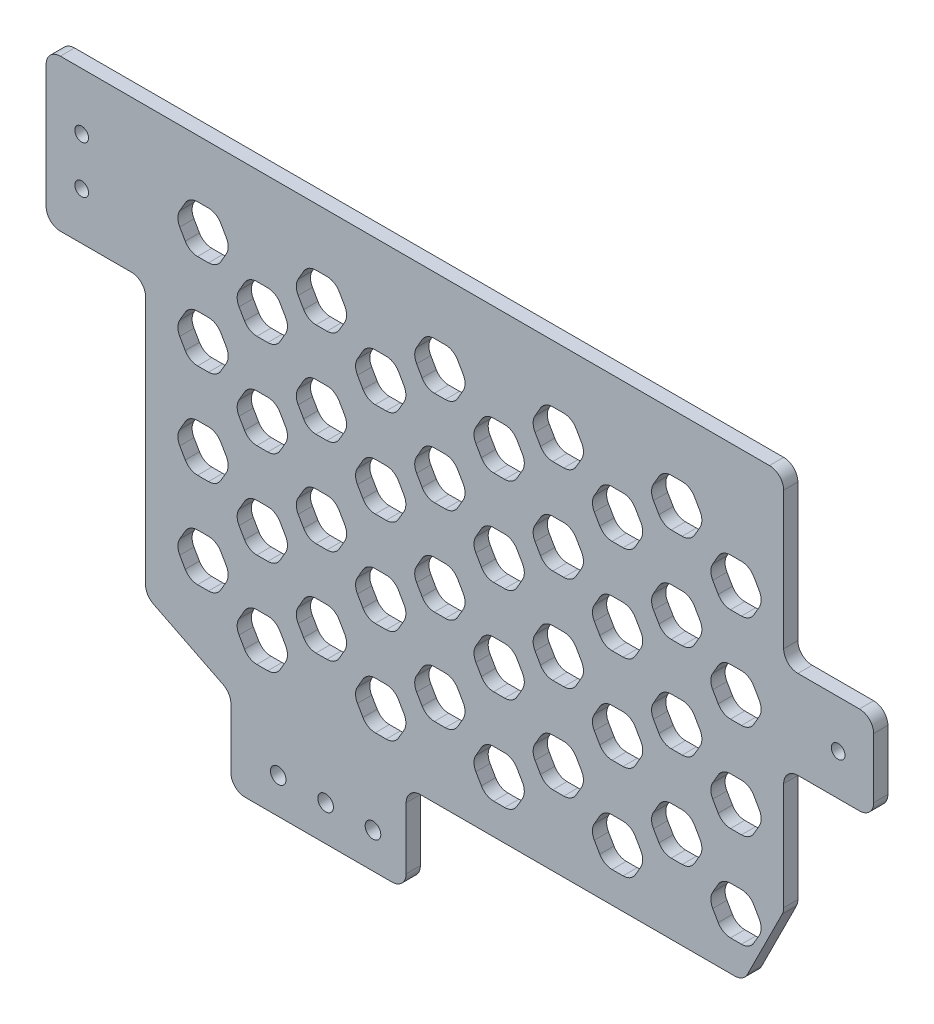
SolidWorks part; units mm, degrees
material "轻木"
ref_plane "前视基准面" through (0, 0, 0) normal (0, 0, 1) x (1, 0, 0)
ref_plane "上视基准面" through (0, 0, 0) normal (0, 1, 0) x (1, 0, 0)
ref_plane "右视基准面" through (0, 0, 0) normal (1, 0, 0) x (0, 0, -1)
other "Configuration Table"
sketch "草图1" plane through (0, 0, 0) normal (0, 0, 1) x (1, 0, 0)
  line L0 (45, -487.5) -> (65, -487.5) construction
  line L1 (415, -487.5) -> (-185, -487.5) construction
  line L2 (65, -487.5) -> (65, -367.5) construction
  line L3 (230, -367.5) -> (0, -367.5) construction
  line L4 (65, -367.5) -> (134.7, -367.5) construction
  line L5 (131.6098, -367.5) -> (70, -367.5) construction
  line L6 (134.7, -367.5) -> (144.6985, -347.503) construction
  line L7 (144.6985, -367.5) -> (144.6985, -7.5) construction
  line L9 (144.6985, -297.5) -> (144.6985, -262.5) construction
  line L10 (144.6985, -262.5) -> (-15, -262.5) construction
  line L11 (-15, -262.5) -> (-15, -302.5) construction
  line L12 (-15, -472.5) -> (-15, 97.5) construction
  line L13 (-15, -302.5) -> (2, -302.5) construction
  line L14 (2, -302.5) -> (2, -347.5) construction
  line L15 (2, -347.5) -> (2, -358.5) construction
  line L16 (17.2361, -366.118) -> (1.0557, -358.0279) construction
  line L17 (2, -358.5) -> (20, -367.5) construction
  line L18 (20, -367.5) -> (20, -382.5) construction
  line L19 (230, -382.5) -> (0, -382.5) construction
  line L20 (20, -382.5) -> (0, -392.5) construction
  line L21 (0, -472.5) -> (0, 97.5) construction
  line L22 (0, -392.5) -> (-15, -392.5) construction
  line L23 (-15, -392.5) -> (-15, -453.5) construction
  line L24 (-15, -453.5) -> (0, -453.5) construction
  line L25 (0, -453.5) -> (0, -470.5) construction
  line L26 (0, -470.5) -> (45, -470.5) construction
  line L27 (45, -470.5) -> (45, -487.5) construction
  line L28 (144.6985, -347.503) -> (144.6985, -324.1459) construction
  line L29 (144.6985, -324.1459) -> (159.7, -324.1459) construction
  line L30 (159.7, -324.1459) -> (159.6985, -297.5) construction
  line L31 (159.6985, -367.5) -> (159.6985, -7.5) construction
  line L32 (159.6985, -297.5) -> (144.6985, -297.5) construction
  line L33 (149.6985, -262.5) -> (158.5181, -262.5) construction
  line L35 (158.5181, -297.5) -> (149.6985, -297.5) construction
  line L36 (143.318, -350.2639) -> (136.082, -364.7361) construction
  line L37 (65, -372.5) -> (65, -482.5) construction
  line L40 (-4, -453.5) -> (-11, -453.5) construction
  line L41 (-10, -392.5) -> (-1.1803, -392.5) construction
  line L42 (1.0557, -391.9721) -> (17.2361, -383.882) construction
  line L43 (140.6985, -301.5) -> (140.6985, -266.5) construction
  line L44 (140.6985, -266.5) -> (-11, -266.5) construction
  line L45 (-11, -266.5) -> (-11, -298.5) construction
  line L46 (-11, -298.5) -> (6, -298.5) construction
  line L47 (6, -298.5) -> (6, -347.5) construction
  line L48 (6, -347.5) -> (6, -356.0279) construction
  line L49 (6, -356.0279) -> (24, -365.0279) construction
  line L50 (24, -365.0279) -> (24, -384.9721) construction
  line L51 (24, -384.9721) -> (0.9443, -396.5) construction
  line L52 (0.9443, -396.5) -> (-11, -396.5) construction
  line L53 (-11, -396.5) -> (-11, -449.5) construction
  line L54 (-11, -449.5) -> (4, -449.5) construction
  line L55 (4, -449.5) -> (4, -466.5) construction
  line L56 (4, -466.5) -> (49, -466.5) construction
  line L57 (49, -466.5) -> (49, -483.5) construction
  line L58 (49, -483.5) -> (61, -483.5) construction
  line L59 (61, -483.5) -> (61, -363.5) construction
  line L60 (61, -363.5) -> (132.2279, -363.5) construction
  line L61 (132.2279, -363.5) -> (140.6985, -346.5588) construction
  line L62 (140.6985, -346.5588) -> (140.6985, -320.1459) construction
  line L63 (140.6985, -320.1459) -> (155.6998, -320.1459) construction
  line L64 (155.6998, -320.1459) -> (155.6987, -301.5) construction
  line L65 (155.6987, -301.5) -> (140.6985, -301.5) construction
  line L66 (-15, -266.5) -> (140.6985, -266.5)
  line L67 (140.6985, -266.5) -> (140.6985, -301.5)
  line L68 (140.6985, -301.5) -> (159.6987, -301.5)
  line L69 (159.6987, -301.5) -> (159.6998, -320.1459)
  line L70 (159.6998, -320.1459) -> (140.6985, -320.1459)
  line L71 (140.6985, -320.1459) -> (140.6985, -346.5588)
  line L72 (140.6985, -346.5588) -> (132.2279, -363.5)
  line L73 (132.2279, -363.5) -> (61, -363.5)
  line L74 (61, -363.5) -> (61, -487.5)
  line L75 (61, -487.5) -> (49, -487.5)
  line L76 (49, -487.5) -> (49, -466.5)
  line L77 (49, -466.5) -> (4, -466.5)
  line L78 (4, -466.5) -> (4, -449.5)
  line L79 (4, -449.5) -> (-15, -449.5)
  line L80 (-15, -449.5) -> (-15, -396.5)
  line L81 (-15, -396.5) -> (0.9443, -396.5)
  line L82 (0.9443, -396.5) -> (24, -384.9721)
  line L83 (24, -384.9721) -> (24, -365.0279)
  line L84 (24, -365.0279) -> (6, -356.0279)
  line L85 (6, -356.0279) -> (6, -298.5)
  line L86 (6, -298.5) -> (-15, -298.5)
  line L87 (-15, -298.5) -> (-15, -266.5)
  dimension "D1" = 4
extrude "凸台-拉伸1" add sketch "草图1" along normal blind 3
sketch "草图2" plane through (0, 0, 3) normal (0, 0, 1) x (1, 0, 0)
  line L2 (-7.5, -251.7939) -> (-7.5, -517.3425) construction
  line L3 (16.6902, -480) -> (92.3332, -480) construction
  line L4 (-15, -298.5) -> (6, -298.5) construction
  line L6 (49, -487.5) -> (61, -487.5) construction
  line L8 (-15, -396.5) -> (-15, -449.5) construction
  line L13 (159.6998, -320.1459) -> (159.6987, -301.5) construction
  line L14 (159.6987, -301.5) -> (140.6985, -301.5) construction
  line L17 (49, -466.5) -> (49, -487.5) construction
  circle A0 centre (-7.5, -415) radius 1.45
  circle A1 centre (-7.5, -439.5) radius 1.45
  circle A2 centre (56, -480) radius 1.45
  circle A5 centre (152.1993, -311.5) radius 1.45
  circle A7 centre (-7.5, -288.5) radius 1.45
  circle A8 centre (-7.5, -278.5) radius 1.45
  dimension "D5" = 126.5
  dimension "D8" = 10
  dimension "D11" = 7
  dimension "D12" = 2.9
  dimension "D13" = 10
  dimension "D14" = 10
  dimension "D3" = 2.9
  dimension "D4" = 24.5
  dimension "D1" = 7.5
  dimension "D2" = 7.5
  dimension "D7" = 7.5
extrude "切除-拉伸1" cut sketch "草图2" against normal through all
fillet "圆角3" radius 3 22 edges at (159.6998, -320.1459, 1.5) (140.6985, -320.1459, 1.5) (61, -487.5, 1.5) (49, -487.5, 1.5) (49, -466.5, 1.5) (4, -466.5, 1.5) (4, -449.5, 1.5) (-15, -449.5, 1.5) (-15, -396.5, 1.5) (0.9443, -396.5, 1.5) (24, -384.9721, 1.5) (24, -365.0279, 1.5) (6, -356.0279, 1.5) (6, -298.5, 1.5) (-15, -298.5, 1.5) (-15, -266.5, 1.5) (140.6985, -266.5, 1.5) (140.6985, -301.5, 1.5) (159.6987, -301.5, 1.5) (140.6985, -346.5588, 1.5) (132.2279, -363.5, 1.5) (61, -363.5, 1.5)
sketch "草图3" plane through (0, 0, 0) normal (0, 0, -1) x (-1, 0, 0)
  circle A0 centre (-34, -375) radius 1.65 construction
  circle A1 centre (-44, -375) radius 1.65 construction
  circle A2 centre (-54, -375) radius 1.65 construction
  circle A3 centre (-34, -375) radius 1.65
  circle A4 centre (-44, -375) radius 1.65
  circle A5 centre (-54, -375) radius 1.65
extrude "切除-拉伸2" cut sketch "草图3" against normal through all
sketch "草图4" plane through (0, 0, 3) normal (0, 0, 1) x (1, 0, 0)
  line L0 (48.8972, -283.6407) -> (46.0104, -278.6407)
  line L1 (23.8972, -283.6407) -> (21.0104, -278.6407)
  line L2 (21.0104, -278.6407) -> (15.2369, -278.6407)
  line L3 (15.2369, -278.6407) -> (12.3502, -283.6407)
  line L4 (12.3502, -283.6407) -> (15.2369, -288.6407)
  line L5 (15.2369, -288.6407) -> (21.0104, -288.6407)
  line L6 (21.0104, -288.6407) -> (23.8972, -283.6407)
  line L7 (36.4102, -291.9675) -> (33.5235, -286.9675)
  line L8 (33.5235, -286.9675) -> (27.75, -286.9675)
  line L9 (27.75, -286.9675) -> (24.8632, -291.9675)
  line L10 (24.8632, -291.9675) -> (27.75, -296.9675)
  line L11 (27.75, -296.9675) -> (33.5235, -296.9675)
  line L12 (33.5235, -296.9675) -> (36.4102, -291.9675)
  line L13 (46.0104, -278.6407) -> (40.2369, -278.6407)
  line L14 (40.2369, -278.6407) -> (37.3502, -283.6407)
  line L15 (37.3502, -283.6407) -> (40.2369, -288.6407)
  line L16 (40.2369, -288.6407) -> (46.0104, -288.6407)
  line L17 (46.0104, -288.6407) -> (48.8972, -283.6407)
  line L18 (61.4102, -291.9675) -> (58.5235, -286.9675)
  line L19 (58.5235, -286.9675) -> (52.75, -286.9675)
  line L20 (52.75, -286.9675) -> (49.8632, -291.9675)
  line L21 (49.8632, -291.9675) -> (52.75, -296.9675)
  line L22 (52.75, -296.9675) -> (58.5235, -296.9675)
  line L23 (58.5235, -296.9675) -> (61.4102, -291.9675)
  line L24 (73.8972, -283.6407) -> (71.0104, -278.6407)
  line L25 (71.0104, -278.6407) -> (65.2369, -278.6407)
  line L26 (65.2369, -278.6407) -> (62.3502, -283.6407)
  line L27 (62.3502, -283.6407) -> (65.2369, -288.6407)
  line L28 (65.2369, -288.6407) -> (71.0104, -288.6407)
  line L29 (71.0104, -288.6407) -> (73.8972, -283.6407)
  line L30 (86.4102, -291.9675) -> (83.5235, -286.9675)
  line L31 (83.5235, -286.9675) -> (77.75, -286.9675)
  line L32 (77.75, -286.9675) -> (74.8632, -291.9675)
  line L33 (74.8632, -291.9675) -> (77.75, -296.9675)
  line L34 (77.75, -296.9675) -> (83.5235, -296.9675)
  line L35 (83.5235, -296.9675) -> (86.4102, -291.9675)
  line L36 (98.8972, -283.6407) -> (96.0104, -278.6407)
  line L37 (96.0104, -278.6407) -> (90.2369, -278.6407)
  line L38 (90.2369, -278.6407) -> (87.3502, -283.6407)
  line L39 (87.3502, -283.6407) -> (90.2369, -288.6407)
  line L40 (90.2369, -288.6407) -> (96.0104, -288.6407)
  line L41 (96.0104, -288.6407) -> (98.8972, -283.6407)
  line L42 (111.4102, -291.9675) -> (108.5235, -286.9675)
  line L43 (108.5235, -286.9675) -> (102.75, -286.9675)
  line L44 (102.75, -286.9675) -> (99.8632, -291.9675)
  line L45 (99.8632, -291.9675) -> (102.75, -296.9675)
  line L46 (102.75, -296.9675) -> (108.5235, -296.9675)
  line L47 (108.5235, -296.9675) -> (111.4102, -291.9675)
  line L48 (123.8972, -283.6407) -> (121.0104, -278.6407)
  line L49 (121.0104, -278.6407) -> (115.2369, -278.6407)
  line L50 (115.2369, -278.6407) -> (112.3502, -283.6407)
  line L51 (112.3502, -283.6407) -> (115.2369, -288.6407)
  line L52 (115.2369, -288.6407) -> (121.0104, -288.6407)
  line L53 (121.0104, -288.6407) -> (123.8972, -283.6407)
  line L54 (136.4102, -291.9675) -> (133.5235, -286.9675)
  line L55 (133.5235, -286.9675) -> (127.75, -286.9675)
  line L56 (127.75, -286.9675) -> (124.8632, -291.9675)
  line L57 (124.8632, -291.9675) -> (127.75, -296.9675)
  line L58 (127.75, -296.9675) -> (133.5235, -296.9675)
  line L59 (133.5235, -296.9675) -> (136.4102, -291.9675)
  line L60 (48.8972, -303.6407) -> (46.0104, -298.6407)
  line L61 (46.0104, -298.6407) -> (40.2369, -298.6407)
  line L62 (40.2369, -298.6407) -> (37.3502, -303.6407)
  line L63 (37.3502, -303.6407) -> (40.2369, -308.6407)
  line L64 (40.2369, -308.6407) -> (46.0104, -308.6407)
  line L65 (46.0104, -308.6407) -> (48.8972, -303.6407)
  line L66 (61.4102, -311.9675) -> (58.5235, -306.9675)
  line L67 (58.5235, -306.9675) -> (52.75, -306.9675)
  line L68 (52.75, -306.9675) -> (49.8632, -311.9675)
  line L69 (49.8632, -311.9675) -> (52.75, -316.9675)
  line L70 (52.75, -316.9675) -> (58.5235, -316.9675)
  line L71 (58.5235, -316.9675) -> (61.4102, -311.9675)
  line L72 (73.8972, -303.6407) -> (71.0104, -298.6407)
  line L73 (71.0104, -298.6407) -> (65.2369, -298.6407)
  line L74 (65.2369, -298.6407) -> (62.3502, -303.6407)
  line L75 (62.3502, -303.6407) -> (65.2369, -308.6407)
  line L76 (65.2369, -308.6407) -> (71.0104, -308.6407)
  line L77 (71.0104, -308.6407) -> (73.8972, -303.6407)
  line L78 (86.4102, -311.9675) -> (83.5235, -306.9675)
  line L79 (83.5235, -306.9675) -> (77.75, -306.9675)
  line L80 (77.75, -306.9675) -> (74.8632, -311.9675)
  line L81 (74.8632, -311.9675) -> (77.75, -316.9675)
  line L82 (77.75, -316.9675) -> (83.5235, -316.9675)
  line L83 (83.5235, -316.9675) -> (86.4102, -311.9675)
  line L84 (98.8972, -303.6407) -> (96.0104, -298.6407)
  line L85 (96.0104, -298.6407) -> (90.2369, -298.6407)
  line L86 (90.2369, -298.6407) -> (87.3502, -303.6407)
  line L87 (87.3502, -303.6407) -> (90.2369, -308.6407)
  line L88 (90.2369, -308.6407) -> (96.0104, -308.6407)
  line L89 (96.0104, -308.6407) -> (98.8972, -303.6407)
  line L90 (111.4102, -311.9675) -> (108.5235, -306.9675)
  line L91 (108.5235, -306.9675) -> (102.75, -306.9675)
  line L92 (102.75, -306.9675) -> (99.8632, -311.9675)
  line L93 (99.8632, -311.9675) -> (102.75, -316.9675)
  line L94 (102.75, -316.9675) -> (108.5235, -316.9675)
  line L95 (108.5235, -316.9675) -> (111.4102, -311.9675)
  line L96 (123.8972, -303.6407) -> (121.0104, -298.6407)
  line L97 (121.0104, -298.6407) -> (115.2369, -298.6407)
  line L98 (115.2369, -298.6407) -> (112.3502, -303.6407)
  line L99 (112.3502, -303.6407) -> (115.2369, -308.6407)
  line L100 (115.2369, -308.6407) -> (121.0104, -308.6407)
  line L101 (121.0104, -308.6407) -> (123.8972, -303.6407)
  line L102 (136.4102, -311.9675) -> (133.5235, -306.9675)
  line L103 (133.5235, -306.9675) -> (127.75, -306.9675)
  line L104 (127.75, -306.9675) -> (124.8632, -311.9675)
  line L105 (124.8632, -311.9675) -> (127.75, -316.9675)
  line L106 (127.75, -316.9675) -> (133.5235, -316.9675)
  line L107 (133.5235, -316.9675) -> (136.4102, -311.9675)
  line L108 (48.8972, -323.6407) -> (46.0104, -318.6407)
  line L109 (46.0104, -318.6407) -> (40.2369, -318.6407)
  line L110 (40.2369, -318.6407) -> (37.3502, -323.6407)
  line L111 (37.3502, -323.6407) -> (40.2369, -328.6407)
  line L112 (40.2369, -328.6407) -> (46.0104, -328.6407)
  line L113 (46.0104, -328.6407) -> (48.8972, -323.6407)
  line L114 (61.4102, -331.9675) -> (58.5235, -326.9675)
  line L115 (58.5235, -326.9675) -> (52.75, -326.9675)
  line L116 (52.75, -326.9675) -> (49.8632, -331.9675)
  line L117 (49.8632, -331.9675) -> (52.75, -336.9675)
  line L118 (52.75, -336.9675) -> (58.5235, -336.9675)
  line L119 (58.5235, -336.9675) -> (61.4102, -331.9675)
  line L120 (73.8972, -323.6407) -> (71.0104, -318.6407)
  line L121 (71.0104, -318.6407) -> (65.2369, -318.6407)
  line L122 (65.2369, -318.6407) -> (62.3502, -323.6407)
  line L123 (62.3502, -323.6407) -> (65.2369, -328.6407)
  line L124 (65.2369, -328.6407) -> (71.0104, -328.6407)
  line L125 (71.0104, -328.6407) -> (73.8972, -323.6407)
  line L126 (86.4102, -331.9675) -> (83.5235, -326.9675)
  line L127 (83.5235, -326.9675) -> (77.75, -326.9675)
  line L128 (77.75, -326.9675) -> (74.8632, -331.9675)
  line L129 (74.8632, -331.9675) -> (77.75, -336.9675)
  line L130 (77.75, -336.9675) -> (83.5235, -336.9675)
  line L131 (83.5235, -336.9675) -> (86.4102, -331.9675)
  line L132 (98.8972, -323.6407) -> (96.0104, -318.6407)
  line L133 (96.0104, -318.6407) -> (90.2369, -318.6407)
  line L134 (90.2369, -318.6407) -> (87.3502, -323.6407)
  line L135 (87.3502, -323.6407) -> (90.2369, -328.6407)
  line L136 (90.2369, -328.6407) -> (96.0104, -328.6407)
  line L137 (96.0104, -328.6407) -> (98.8972, -323.6407)
  line L138 (111.4102, -331.9675) -> (108.5235, -326.9675)
  line L139 (108.5235, -326.9675) -> (102.75, -326.9675)
  line L140 (102.75, -326.9675) -> (99.8632, -331.9675)
  line L141 (99.8632, -331.9675) -> (102.75, -336.9675)
  line L142 (102.75, -336.9675) -> (108.5235, -336.9675)
  line L143 (108.5235, -336.9675) -> (111.4102, -331.9675)
  line L144 (123.8972, -323.6407) -> (121.0104, -318.6407)
  line L145 (121.0104, -318.6407) -> (115.2369, -318.6407)
  line L146 (115.2369, -318.6407) -> (112.3502, -323.6407)
  line L147 (112.3502, -323.6407) -> (115.2369, -328.6407)
  line L148 (115.2369, -328.6407) -> (121.0104, -328.6407)
  line L149 (121.0104, -328.6407) -> (123.8972, -323.6407)
  line L150 (136.4102, -331.9675) -> (133.5235, -326.9675)
  line L151 (133.5235, -326.9675) -> (127.75, -326.9675)
  line L152 (127.75, -326.9675) -> (124.8632, -331.9675)
  line L153 (124.8632, -331.9675) -> (127.75, -336.9675)
  line L154 (127.75, -336.9675) -> (133.5235, -336.9675)
  line L155 (133.5235, -336.9675) -> (136.4102, -331.9675)
  line L156 (48.8972, -343.6407) -> (46.0104, -338.6407)
  line L157 (46.0104, -338.6407) -> (40.2369, -338.6407)
  line L158 (40.2369, -338.6407) -> (37.3502, -343.6407)
  line L159 (37.3502, -343.6407) -> (40.2369, -348.6407)
  line L160 (40.2369, -348.6407) -> (46.0104, -348.6407)
  line L161 (46.0104, -348.6407) -> (48.8972, -343.6407)
  line L162 (61.4102, -351.9675) -> (58.5235, -346.9675)
  line L163 (58.5235, -346.9675) -> (52.75, -346.9675)
  line L164 (52.75, -346.9675) -> (49.8632, -351.9675)
  line L165 (49.8632, -351.9675) -> (52.75, -356.9675)
  line L166 (52.75, -356.9675) -> (58.5235, -356.9675)
  line L167 (58.5235, -356.9675) -> (61.4102, -351.9675)
  line L168 (73.8972, -343.6407) -> (71.0104, -338.6407)
  line L169 (71.0104, -338.6407) -> (65.2369, -338.6407)
  line L170 (65.2369, -338.6407) -> (62.3502, -343.6407)
  line L171 (62.3502, -343.6407) -> (65.2369, -348.6407)
  line L172 (65.2369, -348.6407) -> (71.0104, -348.6407)
  line L173 (71.0104, -348.6407) -> (73.8972, -343.6407)
  line L174 (86.4102, -351.9675) -> (83.5235, -346.9675)
  line L175 (83.5235, -346.9675) -> (77.75, -346.9675)
  line L176 (77.75, -346.9675) -> (74.8632, -351.9675)
  line L177 (74.8632, -351.9675) -> (77.75, -356.9675)
  line L178 (77.75, -356.9675) -> (83.5235, -356.9675)
  line L179 (83.5235, -356.9675) -> (86.4102, -351.9675)
  line L180 (98.8972, -343.6407) -> (96.0104, -338.6407)
  line L181 (96.0104, -338.6407) -> (90.2369, -338.6407)
  line L182 (90.2369, -338.6407) -> (87.3502, -343.6407)
  line L183 (87.3502, -343.6407) -> (90.2369, -348.6407)
  line L184 (90.2369, -348.6407) -> (96.0104, -348.6407)
  line L185 (96.0104, -348.6407) -> (98.8972, -343.6407)
  line L186 (111.4102, -351.9675) -> (108.5235, -346.9675)
  line L187 (108.5235, -346.9675) -> (102.75, -346.9675)
  line L188 (102.75, -346.9675) -> (99.8632, -351.9675)
  line L189 (99.8632, -351.9675) -> (102.75, -356.9675)
  line L190 (102.75, -356.9675) -> (108.5235, -356.9675)
  line L191 (108.5235, -356.9675) -> (111.4102, -351.9675)
  line L192 (123.8972, -343.6407) -> (121.0104, -338.6407)
  line L193 (121.0104, -338.6407) -> (115.2369, -338.6407)
  line L194 (115.2369, -338.6407) -> (112.3502, -343.6407)
  line L195 (112.3502, -343.6407) -> (115.2369, -348.6407)
  line L196 (115.2369, -348.6407) -> (121.0104, -348.6407)
  line L197 (121.0104, -348.6407) -> (123.8972, -343.6407)
  line L198 (136.4102, -351.9675) -> (133.5235, -346.9675)
  line L199 (133.5235, -346.9675) -> (127.75, -346.9675)
  line L200 (127.75, -346.9675) -> (124.8632, -351.9675)
  line L201 (124.8632, -351.9675) -> (127.75, -356.9675)
  line L202 (127.75, -356.9675) -> (133.5235, -356.9675)
  line L203 (133.5235, -356.9675) -> (136.4102, -351.9675)
  line L204 (23.8972, -303.6407) -> (21.0104, -298.6407)
  line L205 (21.0104, -298.6407) -> (15.2369, -298.6407)
  line L206 (15.2369, -298.6407) -> (12.3502, -303.6407)
  line L207 (12.3502, -303.6407) -> (15.2369, -308.6407)
  line L208 (15.2369, -308.6407) -> (21.0104, -308.6407)
  line L209 (21.0104, -308.6407) -> (23.8972, -303.6407)
  line L210 (36.4102, -311.9675) -> (33.5235, -306.9675)
  line L211 (33.5235, -306.9675) -> (27.75, -306.9675)
  line L212 (27.75, -306.9675) -> (24.8632, -311.9675)
  line L213 (24.8632, -311.9675) -> (27.75, -316.9675)
  line L214 (27.75, -316.9675) -> (33.5235, -316.9675)
  line L215 (33.5235, -316.9675) -> (36.4102, -311.9675)
  line L216 (23.8972, -323.6407) -> (21.0104, -318.6407)
  line L217 (21.0104, -318.6407) -> (15.2369, -318.6407)
  line L218 (15.2369, -318.6407) -> (12.3502, -323.6407)
  line L219 (12.3502, -323.6407) -> (15.2369, -328.6407)
  line L220 (15.2369, -328.6407) -> (21.0104, -328.6407)
  line L221 (21.0104, -328.6407) -> (23.8972, -323.6407)
  line L222 (36.4102, -331.9675) -> (33.5235, -326.9675)
  line L223 (33.5235, -326.9675) -> (27.75, -326.9675)
  line L224 (27.75, -326.9675) -> (24.8632, -331.9675)
  line L225 (24.8632, -331.9675) -> (27.75, -336.9675)
  line L226 (27.75, -336.9675) -> (33.5235, -336.9675)
  line L227 (33.5235, -336.9675) -> (36.4102, -331.9675)
  line L228 (23.8972, -343.6407) -> (21.0104, -338.6407)
  line L229 (21.0104, -338.6407) -> (15.2369, -338.6407)
  line L230 (15.2369, -338.6407) -> (12.3502, -343.6407)
  line L231 (12.3502, -343.6407) -> (15.2369, -348.6407)
  line L232 (15.2369, -348.6407) -> (21.0104, -348.6407)
  line L233 (21.0104, -348.6407) -> (23.8972, -343.6407)
  line L234 (36.4102, -351.9675) -> (33.5235, -346.9675)
  line L235 (33.5235, -346.9675) -> (27.75, -346.9675)
  line L236 (27.75, -346.9675) -> (24.8632, -351.9675)
  line L237 (24.8632, -351.9675) -> (27.75, -356.9675)
  line L238 (27.75, -356.9675) -> (33.5235, -356.9675)
  line L239 (33.5235, -356.9675) -> (36.4102, -351.9675)
  line L240 (41.1951, -402.0017) -> (38.3083, -397.0017)
  line L241 (16.1951, -402.0017) -> (13.3083, -397.0017)
  line L242 (13.3083, -397.0017) -> (7.5348, -397.0017)
  line L243 (7.5348, -397.0017) -> (4.6481, -402.0017)
  line L244 (4.6481, -402.0017) -> (7.5348, -407.0017)
  line L245 (7.5348, -407.0017) -> (13.3083, -407.0017)
  line L246 (13.3083, -407.0017) -> (16.1951, -402.0017)
  line L247 (28.5887, -410.5354) -> (25.7019, -405.5354)
  line L248 (25.7019, -405.5354) -> (19.9284, -405.5354)
  line L249 (19.9284, -405.5354) -> (17.0417, -410.5354)
  line L250 (17.0417, -410.5354) -> (19.9284, -415.5354)
  line L251 (19.9284, -415.5354) -> (25.7019, -415.5354)
  line L252 (25.7019, -415.5354) -> (28.5887, -410.5354)
  line L253 (38.3083, -397.0017) -> (32.5348, -397.0017)
  line L254 (32.5348, -397.0017) -> (29.6481, -402.0017)
  line L255 (29.6481, -402.0017) -> (32.5348, -407.0017)
  line L256 (32.5348, -407.0017) -> (38.3083, -407.0017)
  line L257 (38.3083, -407.0017) -> (41.1951, -402.0017)
  line L258 (53.5887, -410.5354) -> (50.7019, -405.5354)
  line L259 (50.7019, -405.5354) -> (44.9284, -405.5354)
  line L260 (44.9284, -405.5354) -> (42.0417, -410.5354)
  line L261 (42.0417, -410.5354) -> (44.9284, -415.5354)
  line L262 (44.9284, -415.5354) -> (50.7019, -415.5354)
  line L263 (50.7019, -415.5354) -> (53.5887, -410.5354)
  line L264 (41.1951, -422.0017) -> (38.3083, -417.0017)
  line L265 (38.3083, -417.0017) -> (32.5348, -417.0017)
  line L266 (32.5348, -417.0017) -> (29.6481, -422.0017)
  line L267 (29.6481, -422.0017) -> (32.5348, -427.0017)
  line L268 (32.5348, -427.0017) -> (38.3083, -427.0017)
  line L269 (38.3083, -427.0017) -> (41.1951, -422.0017)
  line L270 (53.5887, -430.5354) -> (50.7019, -425.5354)
  line L271 (50.7019, -425.5354) -> (44.9284, -425.5354)
  line L272 (44.9284, -425.5354) -> (42.0417, -430.5354)
  line L273 (42.0417, -430.5354) -> (44.9284, -435.5354)
  line L274 (44.9284, -435.5354) -> (50.7019, -435.5354)
  line L275 (50.7019, -435.5354) -> (53.5887, -430.5354)
  line L276 (41.1951, -442.0017) -> (38.3083, -437.0017)
  line L277 (38.3083, -437.0017) -> (32.5348, -437.0017)
  line L278 (32.5348, -437.0017) -> (29.6481, -442.0017)
  line L279 (29.6481, -442.0017) -> (32.5348, -447.0017)
  line L280 (32.5348, -447.0017) -> (38.3083, -447.0017)
  line L281 (38.3083, -447.0017) -> (41.1951, -442.0017)
  line L282 (53.5887, -450.5354) -> (50.7019, -445.5354)
  line L283 (50.7019, -445.5354) -> (44.9284, -445.5354)
  line L284 (44.9284, -445.5354) -> (42.0417, -450.5354)
  line L285 (42.0417, -450.5354) -> (44.9284, -455.5354)
  line L286 (44.9284, -455.5354) -> (50.7019, -455.5354)
  line L287 (50.7019, -455.5354) -> (53.5887, -450.5354)
  line L288 (16.1951, -422.0017) -> (13.3083, -417.0017)
  line L289 (13.3083, -417.0017) -> (7.5348, -417.0017)
  line L290 (7.5348, -417.0017) -> (4.6481, -422.0017)
  line L291 (4.6481, -422.0017) -> (7.5348, -427.0017)
  line L292 (7.5348, -427.0017) -> (13.3083, -427.0017)
  line L293 (13.3083, -427.0017) -> (16.1951, -422.0017)
  line L294 (28.5887, -430.5354) -> (25.7019, -425.5354)
  line L295 (25.7019, -425.5354) -> (19.9284, -425.5354)
  line L296 (19.9284, -425.5354) -> (17.0417, -430.5354)
  line L297 (17.0417, -430.5354) -> (19.9284, -435.5354)
  line L298 (19.9284, -435.5354) -> (25.7019, -435.5354)
  line L299 (25.7019, -435.5354) -> (28.5887, -430.5354)
  line L300 (16.1951, -442.0017) -> (13.3083, -437.0017)
  line L301 (13.3083, -437.0017) -> (7.5348, -437.0017)
  line L302 (7.5348, -437.0017) -> (4.6481, -442.0017)
  line L303 (4.6481, -442.0017) -> (7.5348, -447.0017)
  line L304 (7.5348, -447.0017) -> (13.3083, -447.0017)
  line L305 (13.3083, -447.0017) -> (16.1951, -442.0017)
  line L306 (28.5887, -450.5354) -> (25.7019, -445.5354)
  line L307 (25.7019, -445.5354) -> (19.9284, -445.5354)
  line L308 (19.9284, -445.5354) -> (17.0417, -450.5354)
  line L309 (17.0417, -450.5354) -> (19.9284, -455.5354)
  line L310 (19.9284, -455.5354) -> (25.7019, -455.5354)
  line L311 (25.7019, -455.5354) -> (28.5887, -450.5354)
  line L312 (53.5887, -390.5354) -> (50.7019, -385.5354)
  line L313 (50.7019, -385.5354) -> (44.9284, -385.5354)
  line L314 (44.9284, -385.5354) -> (42.0417, -390.5354)
  line L315 (42.0417, -390.5354) -> (44.9284, -395.5354)
  line L316 (44.9284, -395.5354) -> (50.7019, -395.5354)
  line L317 (50.7019, -395.5354) -> (53.5887, -390.5354)
  circle A0 centre (18.1237, -283.6407) radius 5 construction
  circle A1 centre (30.6367, -291.9675) radius 5 construction
  circle A2 centre (10.4216, -402.0017) radius 5 construction
  circle A3 centre (22.8152, -410.5354) radius 5 construction
  dimension "D1" = 10
  dimension "D2" = 10
  dimension "D7" = 10
  dimension "D8" = 10
  dimension "D3" = 5
  dimension "D6" = 5
  dimension "D4" = 5
  dimension "D5" = 4
  dimension "D9" = 2
  dimension "D10" = 3
  dimension "D11" = 2
extrude "切除-拉伸3" cut sketch "草图4" against normal through all
fillet "圆角4" radius 3 41 edges at (50.7019, -395.5354, 1.5) (44.9284, -415.5354, 1.5) (25.7019, -415.5354, 1.5) (19.9284, -415.5354, 1.5) (29.6481, -402.0017, 1.5) (41.1951, -402.0017, 1.5) (62.3502, -343.6407, 1.5) (77.75, -356.9675, 1.5) (33.5235, -316.9675, 1.5) (115.2369, -348.6407, 1.5) (115.2369, -338.6407, 1.5) (136.4102, -351.9675, 1.5) (38.3083, -437.0017, 1.5) (53.5887, -450.5354, 1.5) (50.7019, -435.5354, 1.5) (50.7019, -425.5354, 1.5) (24.8632, -331.9675, 1.5) (15.2369, -328.6407, 1.5) (12.3502, -323.6407, 1.5) (15.2369, -318.6407, 1.5) (27.75, -346.9675, 1.5) (33.5235, -346.9675, 1.5) (21.0104, -348.6407, 1.5) (133.5235, -336.9675, 1.5) (111.4102, -331.9675, 1.5) (136.4102, -311.9675, 1.5) (121.0104, -298.6407, 1.5) (123.8972, -303.6407, 1.5) (73.8972, -303.6407, 1.5) (16.1951, -442.0017, 1.5) (19.9284, -445.5354, 1.5) (4.6481, -422.0017, 1.5) (7.5348, -417.0017, 1.5) (19.9284, -435.5354, 1.5) (90.2369, -278.6407, 1.5) (62.3502, -283.6407, 1.5) (27.75, -286.9675, 1.5) (58.5235, -296.9675, 1.5) (52.75, -296.9675, 1.5) (49.8632, -291.9675, 1.5) (121.0104, -288.6407, 1.5)
sketch "草图5" plane through (0, 0, 3) normal (0, 0, 1) x (1, 0, 0)
  line L1 (-24.651, -382.5) -> (81.8382, -382.5)
  line L2 (-24.651, -382.5) -> (-24.651, -492.5963)
  line L3 (-24.651, -492.5963) -> (81.8382, -492.5963)
  line L4 (81.8382, -382.5) -> (81.8382, -492.5963)
  circle A0 centre (44, -375) radius 1.65 construction
  dimension "D1" = 7.5
extrude "切除-拉伸4" cut sketch "草图5" against normal through all
fillet "圆角5" radius 3 2 edges at (24, -382.5, 1.5) (61, -382.5, 1.5)
